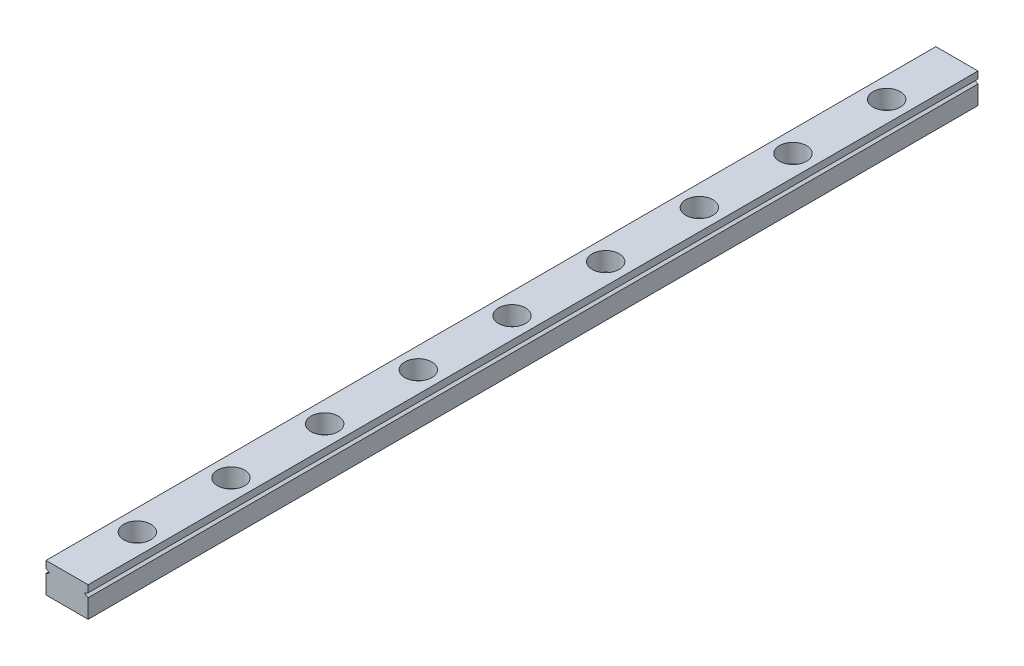
SolidWorks part; units mm, degrees
ref_plane "Front Plane" through (0, 0, 0) normal (0, 0, 1) x (1, 0, 0)
ref_plane "Top Plane" through (0, 0, 0) normal (0, 1, 0) x (1, 0, 0)
ref_plane "Right Plane" through (0, 0, 0) normal (1, 0, 0) x (0, 0, -1)
sketch "Sketch1" plane through (0, 0, 0) normal (0, 0, 1) x (1, 0, 0)
  line L0 (9, 6.4) -> (9, 4.9)
  line L1 (0, 0) -> (9, 0)
  line L2 (0, 0) -> (0, 6.4) construction
  line L3 (0, 6.4) -> (9, 6.4)
  line L4 (9, 0) -> (9, 6.4) construction
  line L5 (9, 4.9) -> (8.2, 4.45)
  line L6 (8.2, 4.45) -> (9, 4)
  line L7 (9, 4) -> (9, 0)
  line L8 (0, 6.4) -> (0, 4.9)
  line L9 (0, 4.9) -> (0.8, 4.45)
  line L10 (0.8, 4.45) -> (0, 4)
  line L11 (0, 4) -> (0, 0)
  line L12 (4.5, 6.4) -> (4.5, 0) construction
  line L13 (9, 4.9) -> (9, 4) construction
  line L14 (9, 4.45) -> (0, 4.45) construction
  dimension "D1" = 9
  dimension "D2" = 6.4
  dimension "D3" = 1.5
  dimension "D4" = 4
  dimension "D5" = 0.8
extrude "Boss-Extrude1" add sketch "Sketch1" along normal blind 190
sketch "Sketch2" plane through (0, 6.4, 0) normal (0, 1, 0) x (1, 0, 0)
  line L0 (4.5, -190) -> (4.5, 0) construction
  line L1 (9, -190) -> (0, -190) construction
  line L2 (9, 0) -> (0, 0) construction
  circle A0 centre (4.5, -175) radius 2.9
  circle A1 centre (4.5, -155) radius 2.9
  circle A2 centre (4.5, -135) radius 2.9
  circle A3 centre (4.5, -115) radius 2.9
  circle A4 centre (4.5, -95) radius 2.9
  circle A5 centre (4.5, -75) radius 2.9
  circle A6 centre (4.5, -55) radius 2.9
  circle A7 centre (4.5, -35) radius 2.9
  circle A8 centre (4.5, -15) radius 2.9
  dimension "D1" = 5.8
  dimension "D2" = 15
  dimension "D3" = 9
extrude "Cut-Extrude1" cut sketch "Sketch2" against normal blind 4
sketch "Sketch3" plane through (0, 2.4, 0) normal (0, 1, 0) x (1, 0, 0)
  circle A0 centre (4.5, -175) radius 1.7
  circle A1 centre (4.5, -175) radius 2.9 construction
  circle A2 centre (4.5, -155) radius 1.7
  circle A3 centre (4.5, -135) radius 1.7
  circle A4 centre (4.5, -115) radius 1.7
  circle A5 centre (4.5, -95) radius 1.7
  circle A6 centre (4.5, -75) radius 1.7
  circle A7 centre (4.5, -55) radius 1.7
  circle A8 centre (4.5, -35) radius 1.7
  circle A9 centre (4.5, -15) radius 1.7
  dimension "D1" = 3.4
  dimension "D2" = 9
extrude "Cut-Extrude2" cut sketch "Sketch3" against normal through all
